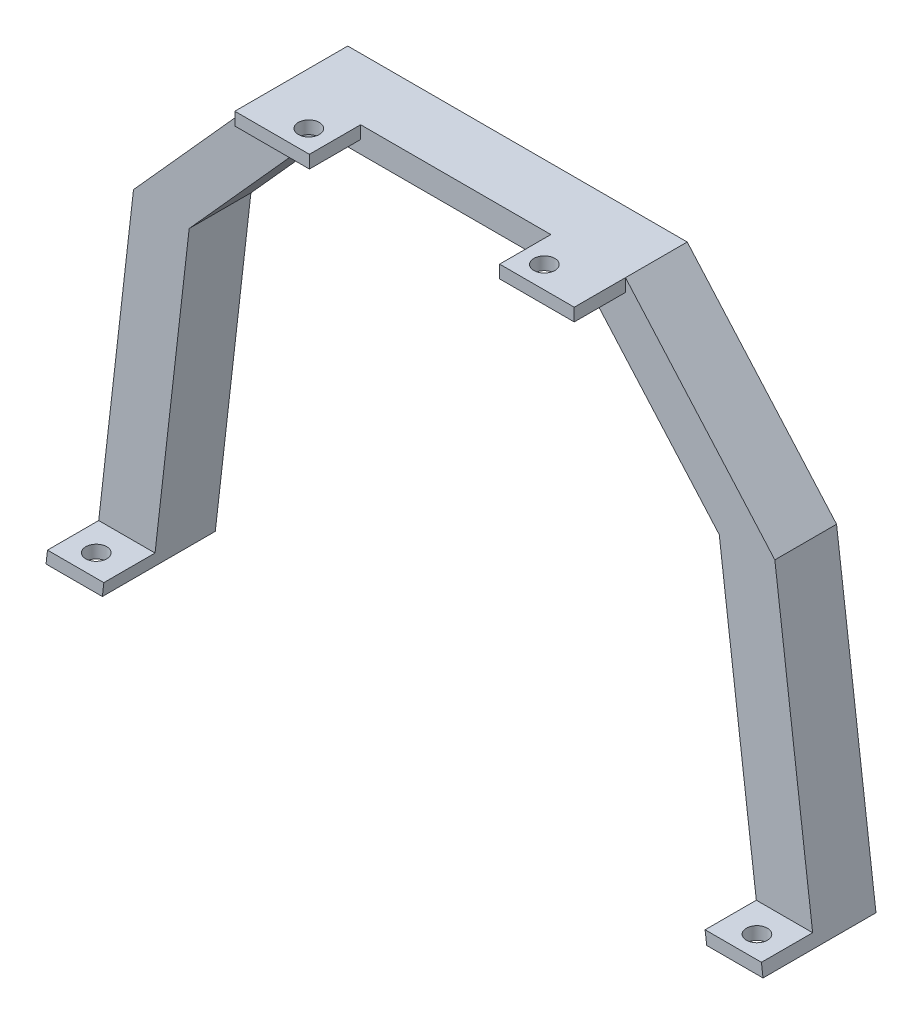
SolidWorks part; units mm, degrees
ref_plane "Front Plane" through (0, 0, 0) normal (0, 0, 1) x (1, 0, 0)
ref_plane "Top Plane" through (0, 0, 0) normal (0, 1, 0) x (1, 0, 0)
ref_plane "Right Plane" through (0, 0, 0) normal (1, 0, 0) x (0, 0, -1)
sketch "Sketch1" plane through (0, 0, 0) normal (0, 0, 1) x (1, 0, 0)
  line L0 (0, 0) -> (-11, 0)
  line L2 (118, 0) -> (129, 0)
  line L3 (-11, 0) -> (-3.9166, 61.8579)
  line L16 (-3.9166, 61.8579) -> (25.8602, 95)
  line L17 (25.8602, 95) -> (92.1398, 95)
  line L18 (92.1398, 95) -> (121.306, 61.8579)
  line L19 (121.306, 61.8579) -> (129, 0)
  line L20 (0, 0) -> (6.9518, 60.7091)
  line L21 (6.9518, 60.7091) -> (33.2685, 90)
  line L22 (33.2685, 90) -> (84.6719, 90)
  line L23 (84.6719, 90) -> (110.4489, 60.7091)
  line L24 (110.4489, 60.7091) -> (118, 0)
  point P26 (59, 95)
  dimension "D1" = 140
  dimension "D2" = 11
  dimension "D3" = 90
  dimension "D4" = 70
  dimension "D5" = 5
extrude "Boss-Extrude1" add sketch "Sketch1" along normal blind 10 and the other way blind 2.0551
sketch "Sketch2" plane through (0, 0, 10) normal (0, 0, 1) x (1, 0, 0)
  line L0 (-11, 0) -> (0, 0)
  line L1 (0, 0) -> (0.2863, 2.5)
  line L2 (0, 0) -> (6.9518, 60.7091) construction
  line L3 (0.2863, 2.5) -> (-10.7137, 2.5)
  line L4 (-3.9166, 61.8579) -> (-11, 0) construction
  line L5 (-10.7137, 2.5) -> (-11, 0)
  line L6 (118, 0) -> (129, 0)
  line L7 (129, 0) -> (128.689, 2.5)
  line L8 (129, 0) -> (121.306, 61.8579) construction
  line L9 (128.689, 2.5) -> (117.689, 2.5)
  line L10 (110.4489, 60.7091) -> (118, 0) construction
  line L11 (117.689, 2.5) -> (118, 0)
  point P14 (-5.5, 0)
  dimension "D1" = 2.5
  dimension "D2" = 2.5
extrude "Boss-Extrude2" add sketch "Sketch2" along normal blind 10
sketch "Sketch3" plane through (0, 2.5, 0) normal (0, 1, 0) x (1, 0, 0)
  line L0 (-11, -20) -> (-11, 2.0551) construction
  line L1 (129, -20) -> (129, 2.0551) construction
  circle A0 centre (-5.5, -15.6874) radius 2.05
  circle A1 centre (123.5, -15.6874) radius 2.05
  dimension "D3" = 4.1
  dimension "D1" = 5.5
  dimension "D2" = 5.5
extrude "Cut-Extrude1" cut sketch "Sketch3" against normal blind 10
sketch "Sketch4" plane through (0, 0, 10) normal (0, 0, 1) x (1, 0, 0)
  line L0 (-11, 0) -> (59, 0)
  line L1 (25.8602, 95) -> (40.4285, 95)
  line L2 (25.8602, 95) -> (25.8602, 92.5)
  line L3 (25.8602, 92.5) -> (40.4285, 92.5)
  line L4 (40.4285, 95) -> (40.4285, 92.5)
  line L9 (59, 0) -> (59, 79.0988)
  line L10 (77.5715, 95) -> (77.5715, 92.5)
  line L11 (92.1398, 92.5) -> (77.5715, 92.5)
  line L12 (92.1398, 95) -> (92.1398, 92.5)
  line L13 (92.1398, 95) -> (77.5715, 95)
  dimension "D1" = 140
  dimension "D2" = 70
  dimension "D3" = 2.5
extrude "Boss-Extrude3" add sketch "Sketch4" along normal blind 10 contours L3 L4 L1 L2 | L13 L10 L11 L12
sketch "Sketch6" plane through (0, 95, 0) normal (0, 1, 0) x (1, 0, 0)
  line L2 (-11, -20) -> (-11, 2.0551) construction
  line L3 (59, -10) -> (59, 2.0551)
  line L4 (77.5715, -10) -> (40.4285, -10) construction
  line L5 (92.1398, 2.0551) -> (25.8602, 2.0551) construction
  circle A0 centre (36, -15.6874) radius 2.05
  circle A1 centre (82, -15.6874) radius 2.05
  circle A7 centre (-5.5, -15.6874) radius 2.05
  dimension "D2" = 4.1
  dimension "D1" = 23
  dimension "D3" = 70
extrude "Cut-Extrude2" cut sketch "Sketch6" against normal blind 10 contours A0 | A1
